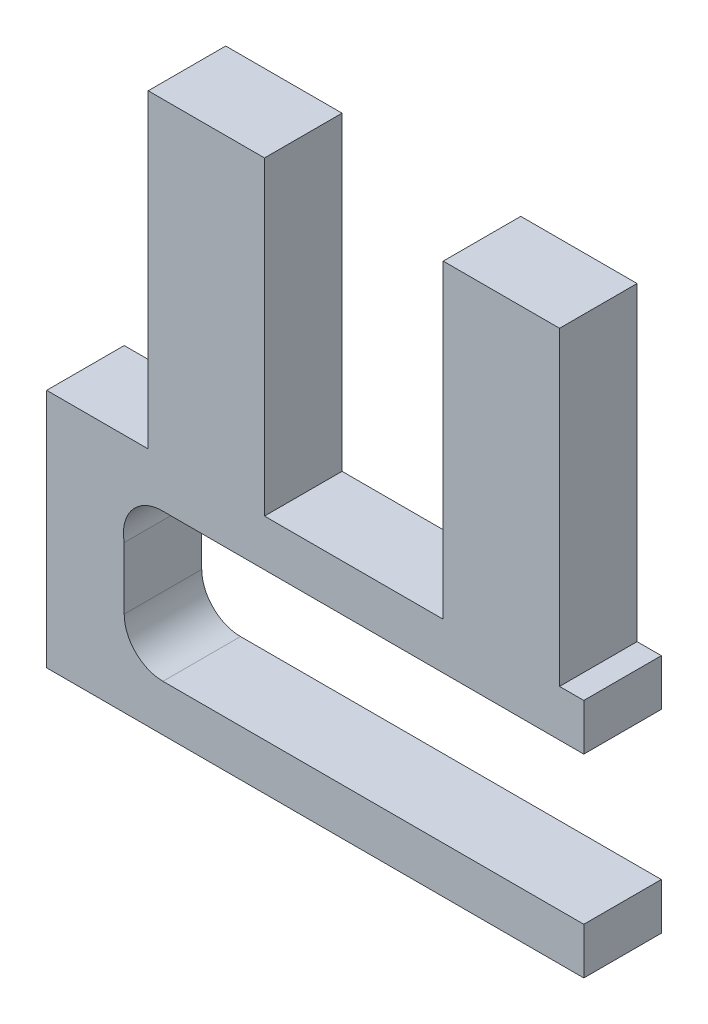
SolidWorks part; units mm, degrees
ref_plane "前基準面" through (0, 0, 0) normal (0, 0, 1) x (1, 0, 0)
ref_plane "上基準面" through (0, 0, 0) normal (0, 1, 0) x (1, 0, 0)
ref_plane "右基準面" through (0, 0, 0) normal (1, 0, 0) x (0, 0, -1)
sketch "草圖1" plane through (0, 0, 0) normal (0, 0, 1) x (1, 0, 0)
  line L10 (-15.54, 30.4955) -> (-15.54, 30.5896)
  line L12 (-7.54, 22.3247) -> (-7.54, 1.4189)
  line L13 (-7.54, 32.4189) -> (5.5532, 32.4189)
  line L15 (7.46, 26.4189) -> (61.7301, 26.4189)
  line L16 (61.7301, 32.4189) -> (61.7301, 26.4189)
  line L17 (7.46, 7.4189) -> (61.7301, 7.4189)
  line L19 (-7.54, 1.4189) -> (61.7301, 1.4189)
  line L20 (61.7301, 7.4189) -> (61.7301, 1.4189)
  line L24 (2.46, 20.4189) -> (2.46, 12.4189)
  line L25 (-7.54, 22.3247) -> (-7.54, 32.4189)
  line L27 (58.6012, 32.4189) -> (58.6012, 72.4189)
  line L28 (58.6012, 72.4189) -> (43.6012, 72.4189)
  line L29 (43.6012, 32.4189) -> (43.6012, 72.4189)
  line L30 (58.6012, 32.4189) -> (61.7301, 32.4189)
  line L33 (20.5532, 32.4189) -> (20.5532, 72.4189)
  line L34 (20.5532, 72.4189) -> (5.5532, 72.4189)
  line L35 (5.5532, 32.4189) -> (5.5532, 72.4189)
  line L36 (20.5532, 32.4189) -> (43.6012, 32.4189)
  arc A0 (7.46, 26.4189) -> (2.46, 20.4189) centre (7.3587, 21.4199) ccw
  arc A1 (7.46, 7.4189) -> (2.46, 12.4189) centre (7.46, 12.4189) cw
  dimension "D3" = 40
  dimension "D4" = 15
  dimension "D5" = 6
  dimension "D6" = 6
  dimension "D7" = 15
  dimension "D11" = 19
extrude "填料-伸長1" add sketch "草圖1" along normal blind 10 contours L17 A1 L24 A0 L15 L16 L30 L27 L28 L29 L36 L33 L34 L35 L13 L25 L12 L19 L20
